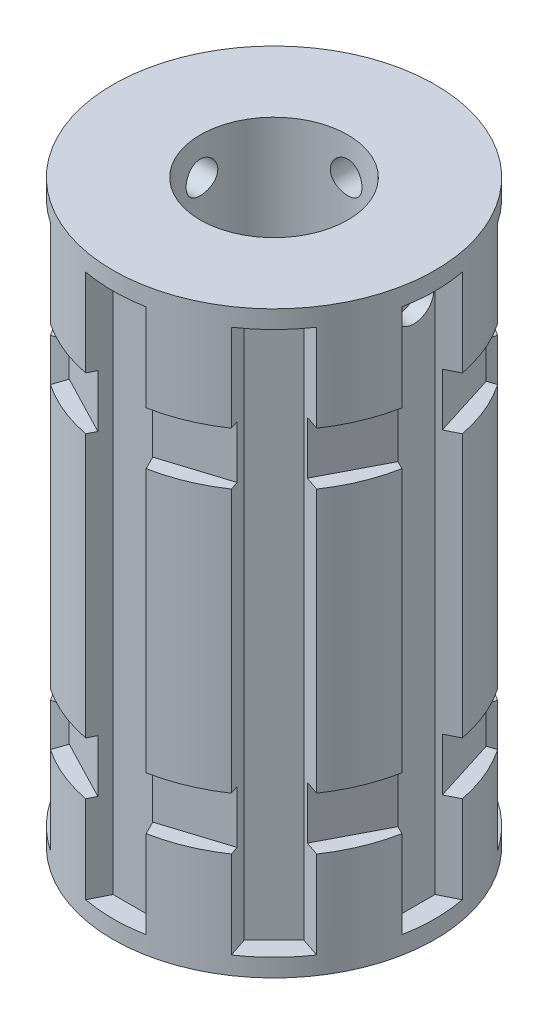
SolidWorks part; units mm, degrees
ref_plane "Front Plane" through (0, 0, 0) normal (0, 0, 1) x (1, 0, 0)
ref_plane "Top Plane" through (0, 0, 0) normal (0, 1, 0) x (1, 0, 0)
ref_plane "Right Plane" through (0, 0, 0) normal (1, 0, 0) x (0, 0, -1)
sketch "Sketch1" plane through (0, 0, 0) normal (0, 1, 0) x (1, 0, 0)
  line L0 (0, 0) -> (0, 3.15) construction
  line L1 (0, 3.15) -> (0, -3.15) construction
  line L2 (0, -3.15) -> (3.15, 0) construction
  line L3 (3.15, 0) -> (-3.15, 0) construction
  line L4 (-3.15, 0) -> (0, 3.15) construction
  line L5 (0, 3.15) -> (3.15, 0) construction
  line L6 (-3.15, 0) -> (0, -3.15) construction
  line L7 (0, 0) -> (-1.9164, 2.5) construction
  line L8 (-1.9164, 2.5) -> (-1.9164, -2.5) construction
  line L9 (-1.9164, -2.5) -> (1.9164, -2.5) construction
  line L10 (1.9164, -2.5) -> (1.9164, 2.5) construction
  line L11 (1.9164, 2.5) -> (-1.9164, 2.5)
  arc A0 (-1.9164, 2.5) -> (1.9164, 2.5) centre (0, 0) ccw
  circle A1 centre (0, 0) radius 15.2785
  point P1 (0, 2.5)
  dimension "D1" = 6.3
  dimension "D2" = 30.557
  dimension "D3" = 5.65
extrude "Boss-Extrude1" add sketch "Sketch1" along normal blind 55
ref_plane "Plane1" through (0, 27.5, 0) normal (0, -1, 0) x (-1, 0, 0)
sketch "Sketch3" plane through (0, 27.5, 0) normal (0, -1, 0) x (-1, 0, 0)
  line L0 (0, 15.2785) -> (0, 13.2785) construction
  line L1 (-2, 13.2785) -> (2, 13.2785)
  line L2 (2, 13.2785) -> (3, 15.2785)
  line L3 (3, 15.2785) -> (-3, 15.2785)
  line L4 (-3, 15.2785) -> (-2, 13.2785)
  line L5 (0, 0) -> (0, 15.2785) construction
  circle A3 centre (0, 0) radius 15.2785 construction
  point P8 (0, 13.2785)
  point P10 (0, 15.2785)
  dimension "D1" = 6
  dimension "D2" = 4
  dimension "D4" = 2
extrude "Cut-Extrude2" cut sketch "Sketch3" against normal blind 25.8 and the other way blind 25.8
ref_axis "Axis1" through (0, 119.4093, 0) along (0, -1, 0)
pattern_circular "CirPattern1" count 8 over 360 about axis through (0, 0, 0) along (0, 1, 0) of "Cut-Extrude2"
sketch "Sketch5" plane through (0, 55, 0) normal (0, 1, 0) x (1, 0, 0)
  circle A0 centre (0, 0) radius 7.005
  dimension "D1" = 14.01
extrude "Cut-Extrude3" cut sketch "Sketch5" against normal through all
ref_plane "Plane2" through (0, 0, 0) normal (0.887, 0, 0.4617) x (0, -1, 0)
sketch "Sketch7" plane through (0, 0, 0) normal (0.887, 0, 0.4617) x (0, -1, 0)
  line L0 (0, 15.2785) -> (-55, 15.2785) construction
  line L1 (-10, 15.2785) -> (-15, 15.2785)
  line L2 (-10, 15.2785) -> (-10, 13.7785)
  line L3 (-10, 13.7785) -> (-15, 13.7785)
  line L4 (-15, 15.2785) -> (-15, 13.7785)
  line L5 (0, -15.2785) -> (0, 15.2785) construction
  line L6 (-55, 15.2785) -> (-55, -15.2785) construction
  line L7 (-45, 15.2785) -> (-40, 15.2785)
  line L8 (-45, 15.2785) -> (-45, 13.7785)
  line L9 (-45, 13.7785) -> (-40, 13.7785)
  line L10 (-40, 15.2785) -> (-40, 13.7785)
  dimension "D1" = 5
  dimension "D2" = 1.5
  dimension "D3" = 10
  dimension "D4" = 10
  dimension "D5" = 5
  dimension "D6" = 1.5
extrude "Cut-Extrude4" cut sketch "Sketch7" along normal through all both and the other way through all
pattern_circular "CirPattern2" count 8 over 360 about axis through (0, 0, 0) along (0, 1, 0) of "Cut-Extrude4"
sketch "Sketch8" plane through (13.2785, 0, 0) normal (1, 0, 0) x (0, 0, -1)
  line L0 (2, 1.7) -> (2, 53.3) construction
  line L1 (15.2785, 55) -> (-15.2785, 55) construction
  circle A0 centre (0, 51.5) radius 1.9
  dimension "D1" = 3.8
  dimension "D2" = 2
  dimension "D3" = 3.5
extrude "Cut-Extrude5" cut sketch "Sketch8" against normal blind 1.5
pattern_circular "CirPattern3" count 2 over 360 about axis through (0, 119.4093, 0) along (0, -1, 0) of "Cut-Extrude5"
sketch "Sketch9" plane through (0, 0, -13.2785) normal (0, 0, -1) x (-1, 0, 0)
  line L0 (0, 16.8063) -> (0, -16.8063) construction
  line L1 (2, 1.7) -> (2, 53.3) construction
  line L2 (15.2785, 55) -> (-15.2785, 55) construction
  circle A0 centre (0, 51.5) radius 1.9
  dimension "D1" = 2
  dimension "D3" = 3.8
  dimension "D2" = 3.5
extrude "Cut-Extrude6" cut sketch "Sketch9" against normal blind 1.5
sketch "Sketch10" plane through (11.7785, 0, 0) normal (1, 0, 0) x (0, 0, -1)
  circle A0 centre (0, 51.5) radius 1.505
  dimension "D1" = 3.01
extrude "Cut-Extrude7" cut sketch "Sketch10" against normal through all
sketch "Sketch11" plane through (0, 0, -11.7785) normal (0, 0, -1) x (-1, 0, 0)
  circle A0 centre (0, 51.5) radius 1.505
  dimension "D1" = 3.01
extrude "Cut-Extrude8" cut sketch "Sketch11" against normal blind 8
